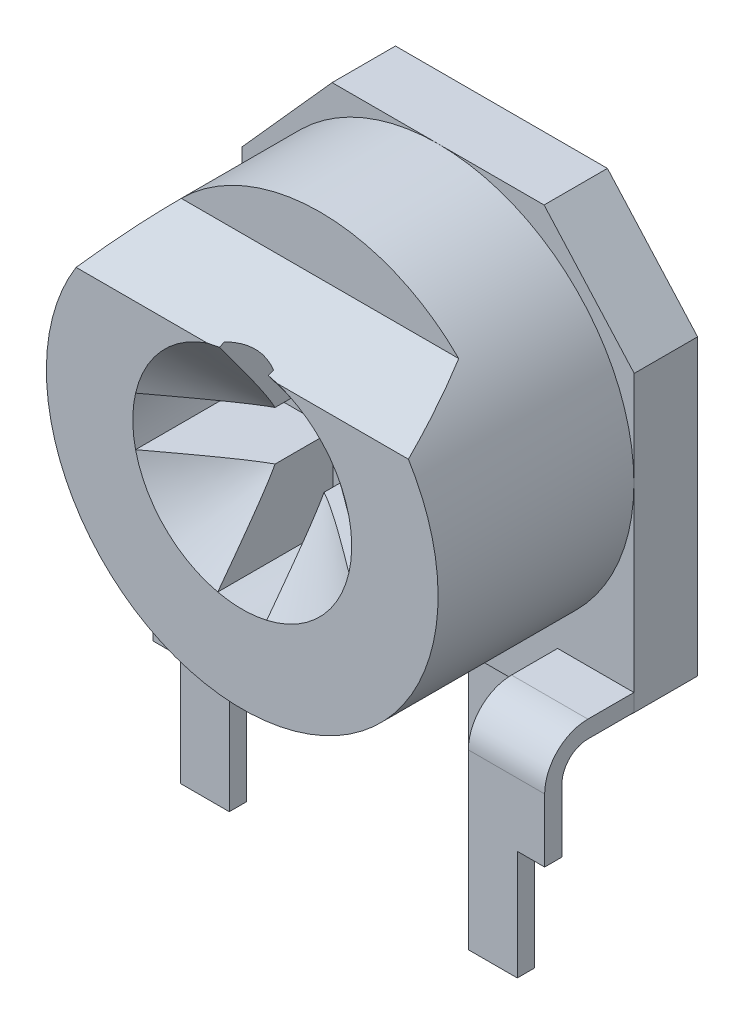
SolidWorks part; units mm, degrees
ref_plane "Front Plane" through (0, 0, 0) normal (0, 0, 1) x (1, 0, 0)
ref_plane "Top Plane" through (0, 0, 0) normal (0, 1, 0) x (1, 0, 0)
ref_plane "Right Plane" through (0, 0, 0) normal (1, 0, 0) x (0, 0, -1)
sketch "Sketch1" plane through (0, 0, 0) normal (0, 0, 1) x (1, 0, 0)
  line L0 (-1.84, 8.4) -> (-3.405, 6.65)
  line L1 (-1.84, 8.4) -> (1.84, 8.4)
  line L2 (-3.405, 6.65) -> (-3.405, 1.55)
  line L3 (-2.8, 1) -> (2.8, 1)
  line L4 (3.405, 6.65) -> (3.405, 1.55)
  line L5 (0, 1) -> (0, 0) construction
  line L6 (0, 1) -> (0, 8.4) construction
  line L7 (1.84, 8.4) -> (3.405, 6.65)
  line L8 (-3.405, 1.55) -> (-2.8, 1)
  line L9 (3.405, 1.55) -> (2.8, 1)
  dimension "D1" = 1.75
  dimension "D2" = 6.81
  dimension "D3" = 1
  dimension "D4" = 0.55
  dimension "D5" = 5.6
  dimension "D6" = 3.68
  dimension "D7" = 8.4
extrude "Boss-Extrude1" add sketch "Sketch1" along normal blind 1.1
sketch "Sketch2" plane through (0, 0, 1.1) normal (0, 0, 1) x (1, 0, 0)
  line L0 (0, 5) -> (0, 0) construction
  circle A0 centre (0, 5) radius 3.4
  dimension "D1" = 5
  dimension "D2" = 6.8
extrude "Boss-Extrude2" add sketch "Sketch2" along normal offset from surface (3.4 mm away) 4.5 up to face at (0, 4.4, 0)
sketch "Sketch3" plane through (0, 0, 0) normal (1, 0, 0) x (0, 0, -1)
  line L0 (-3.15, 8.4) -> (-3.15, 7.4)
  line L1 (-1.1, 8.4) -> (-4.5, 8.4) construction
  line L2 (-3.15, 7.4) -> (-4.5, 6.8)
  line L3 (-4.5, 8.4) -> (-4.5, 1.6) construction
  line L4 (-4.5, 6.8) -> (-4.5, 8.4)
  line L5 (-4.5, 8.4) -> (-3.15, 8.4)
  dimension "D1" = 1.35
  dimension "D2" = 1.6
  dimension "D3" = 1
extrude "Cut-Extrude1" cut sketch "Sketch3" against normal through all and the other way through all
ref_plane "Plane1" through (0, 5, 0) normal (0, 1, 0) x (-1, 0, 0)
sketch "Sketch5" plane through (0, 5, 0) normal (0, 1, 0) x (-1, 0, 0)
  line L0 (0, 4.5) -> (-1.9, 4.5)
  line L2 (-2.8844, 4.5) -> (2.8844, 4.5) construction
  line L3 (-1.9, 4.5) -> (-0.425, 3.37)
  line L4 (-0.425, 3.37) -> (0, 3.37)
  line L5 (0, 3.37) -> (0, 4.5)
  dimension "D1" = 1.9
  dimension "D2" = 1.13
  dimension "D3" = 0.425
revolve "Cut-Revolve1" cut sketch "Sketch5" angle 360 about L5
sketch "Sketch6" plane through (0, 0, 4.5) normal (0, 0, 1) x (1, 0, 0)
  line L0 (0.425, 5.425) -> (1.8519, 5.425)
  line L1 (-1.8519, 4.575) -> (-0.425, 4.575)
  line L2 (0.425, 4.575) -> (0.425, 3.1481)
  line L3 (-1.8519, 5.425) -> (-0.425, 5.425)
  line L4 (0.425, 4.575) -> (1.8519, 4.575)
  line L5 (-2.3596, 4.575) -> (2.3596, 5.425) construction
  line L6 (-2.3596, 5.425) -> (2.3596, 4.575) construction
  line L7 (-0.425, 4.575) -> (-0.425, 3.1481)
  line L8 (-0.425, 6.8519) -> (-0.425, 5.425)
  line L10 (0.425, 6.8519) -> (0.425, 5.425)
  line L11 (-0.425, 7.1442) -> (0.425, 2.8558) construction
  line L12 (-0.425, 2.8558) -> (0.425, 7.1442) construction
  arc A0 (-0.6083, 6.8) -> (0.6083, 6.8) centre (0, 5) ccw construction
  arc A1 (-1.8519, 5.425) -> (-1.8519, 4.575) centre (0, 5) ccw
  arc A2 (0.425, 6.8519) -> (-0.425, 6.8519) centre (0, 5) ccw
  arc A3 (1.8519, 4.575) -> (1.8519, 5.425) centre (0, 5) ccw
  arc A4 (-0.425, 3.1481) -> (0.425, 3.1481) centre (0, 5) ccw
  point P0 (0, 5)
  point P5 (0, 5)
  dimension "D1" = 0.85
extrude "Cut-Extrude2" cut sketch "Sketch6" against normal blind 2
sketch "Sketch7" plane through (0, 0, 0) normal (0, 0, 1) x (1, 0, 0)
  line L2 (-0.425, 0.21) -> (-0.425, -1.905)
  line L3 (-0.425, -1.905) -> (0.425, -1.905)
  line L4 (0.425, 0.21) -> (0.425, -1.905)
  line L5 (-0.425, 2.0745) -> (0.425, -1.905) construction
  line L6 (-0.425, -1.905) -> (0.425, 2.0745) construction
  line L7 (-0.875, 1) -> (-0.875, 0.21)
  line L8 (-2.8, 1) -> (2.8, 1) construction
  line L9 (-0.875, 0.21) -> (-0.425, 0.21)
  line L10 (0.875, 0.21) -> (0.875, 1)
  line L11 (0.425, 0.21) -> (0.875, 0.21)
  arc A0 (-0.875, 1) -> (0.875, 1) centre (0, 1) cw
  point P0 (0, 0.0848)
  dimension "D4" = 0.79
  dimension "D1" = 1.905
  dimension "D2" = 0.85
  dimension "D3" = 1.75
extrude "Boss-Extrude3" add sketch "Sketch7" along normal mid plane 0.3
sketch "Sketch8" plane through (0, 0, 0) normal (1, 0, 0) x (0, 0, -1)
  line L1 (0, 1.85) -> (-1.9, 1.85)
  line L2 (0, 1.85) -> (0, 1.55)
  line L3 (-2.35, -1.905) -> (-2.65, -1.905)
  line L4 (-2.65, 1.1) -> (-2.65, -1.905)
  line L5 (0, 1.55) -> (0, 6.65) construction
  line L7 (0, 1.55) -> (-1.9, 1.55)
  line L8 (-2.35, 1.1) -> (-2.35, -1.905)
  line L9 (-0.15, -1.905) -> (0.15, -1.905) construction
  line L10 (-1.1, 1.55) -> (0, 1.55) construction
  line L11 (0.15, -1.905) -> (0.15, 0.21) construction
  arc A0 (-1.9, 1.85) -> (-2.65, 1.1) centre (-1.9, 1.1) ccw
  arc A1 (-1.9, 1.55) -> (-2.35, 1.1) centre (-1.9, 1.1) ccw
  dimension "D3" = 0.75
  dimension "D1" = 0.3
  dimension "D2" = 2.5
extrude "Boss-Extrude4" add sketch "Sketch8" along normal mid plane 6.8
sketch "Sketch9" plane through (0, 0, 4.5) normal (0, 0, 1) x (1, 0, 0)
  line L0 (-2.075, -1.905) -> (-2.075, 2.3066)
  line L1 (3.4, -1.905) -> (-3.4, -1.905) construction
  line L2 (2.075, -1.905) -> (2.075, 2.3066)
  line L3 (-2.075, -1.905) -> (2.075, -1.905)
  line L4 (0, 0) -> (0, -1.905) construction
  arc A0 (-2.8844, 6.8) -> (2.8844, 6.8) centre (0, 5) ccw construction
  arc A1 (-2.075, 2.3066) -> (2.075, 2.3066) centre (0, 5) ccw
  dimension "D1" = 4.15
extrude "Cut-Extrude3" cut sketch "Sketch9" against normal up to surface (3.4 mm away)
sketch "Sketch10" plane through (0, 0, 2.65) normal (0, 0, 1) x (1, 0, 0)
  line L0 (-3.4, 1.1) -> (-3.4, -1.905) construction
  line L1 (-3.4, 0) -> (-2.925, 0)
  line L2 (-3.4, 0) -> (-3.4, -1.905)
  line L3 (-3.4, -1.905) -> (-2.925, -1.905)
  line L4 (-2.925, 0) -> (-2.925, -1.905)
  line L5 (-2.075, -1.905) -> (-3.4, -1.905) construction
  line L6 (3.4, 1.1) -> (3.4, -1.905) construction
  line L7 (3.4, 0) -> (2.925, 0)
  line L8 (3.4, 0) -> (3.4, -1.905)
  line L9 (3.4, -1.905) -> (2.925, -1.905)
  line L10 (2.925, 0) -> (2.925, -1.905)
  line L11 (3.4, -1.905) -> (2.075, -1.905) construction
  line L12 (-2.075, -1.905) -> (-2.075, 1.1) construction
  dimension "D1" = 0.85
extrude "Cut-Extrude4" cut sketch "Sketch10" against normal through all
